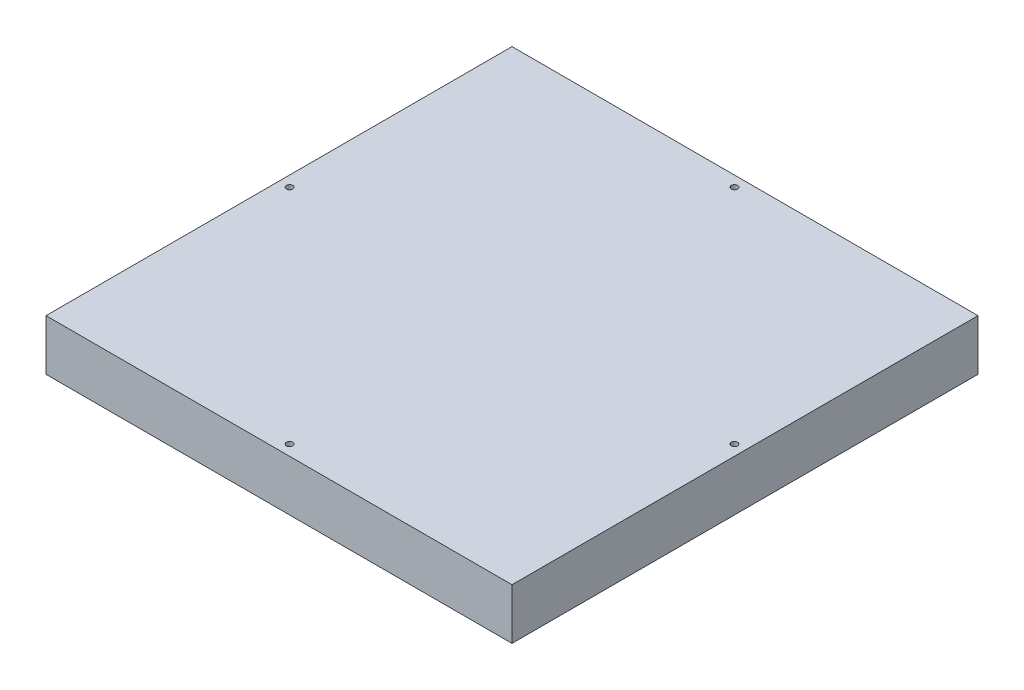
SolidWorks part; units mm, degrees
material "Oak"
ref_plane "Front Plane" through (0, 0, 0) normal (0, 0, 1) x (1, 0, 0)
ref_plane "Top Plane" through (0, 0, 0) normal (0, 1, 0) x (1, 0, 0)
ref_plane "Right Plane" through (0, 0, 0) normal (1, 0, 0) x (0, 0, -1)
sketch "Sketch1" plane through (0, 0, 0) normal (0, 1, 0) x (1, 0, 0)
  line L0 (-105, 0) -> (105, 0) construction
  line L1 (-110, -110) -> (110, -110)
  line L2 (-110, -110) -> (-110, 110)
  line L3 (-110, 110) -> (110, 110)
  line L4 (110, -110) -> (110, 110)
  line L5 (-110, -110) -> (110, 110) construction
  line L6 (-110, 110) -> (110, -110) construction
  line L7 (-105, -105) -> (105, -105) construction
  line L8 (-105, -105) -> (-105, 105) construction
  line L9 (-105, 105) -> (105, 105) construction
  line L10 (105, -105) -> (105, 105) construction
  line L11 (-105, -105) -> (105, 105) construction
  line L12 (-105, 105) -> (105, -105) construction
  line L14 (0, 105) -> (0, -105) construction
  circle A1 centre (-105, 0) radius 1.5
  circle A3 centre (105, 0) radius 1.5
  circle A5 centre (0, -105) radius 1.5
  circle A7 centre (0, 105) radius 1.5
  point P0 (-105.1948, 0.3897)
  point P1 (0, 0)
  point P13 (0, 0)
  point P19 (-105, 0)
  point P20 (0, -105)
  dimension "D4" = 3
  dimension "D1" = 220
  dimension "D3" = 210
extrude "Boss-Extrude1" add sketch "Sketch1" along normal blind 24
